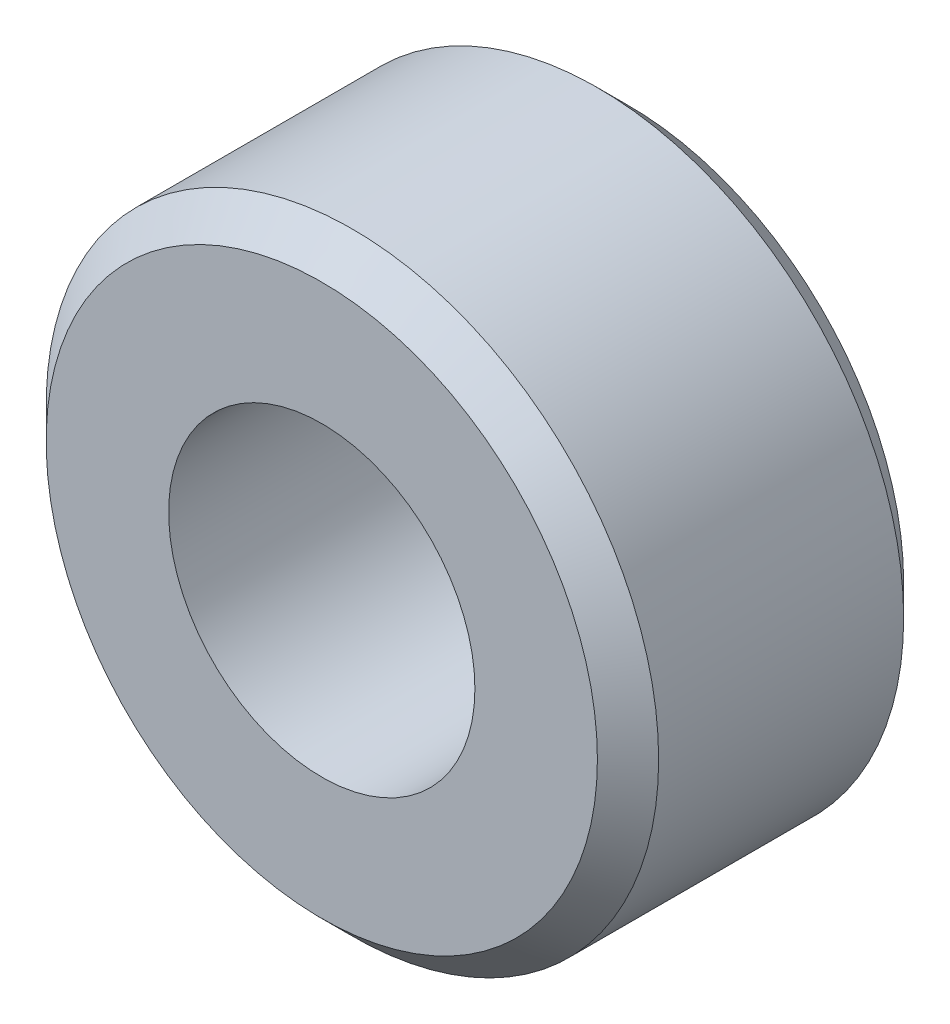
SolidWorks part; units mm, degrees
ref_plane "Płaszczyzna przednia" through (0, 0, 0) normal (0, 0, 1) x (1, 0, 0)
ref_plane "Płaszczyzna górna" through (0, 0, 0) normal (0, 1, 0) x (1, 0, 0)
ref_plane "Płaszczyzna prawa" through (0, 0, 0) normal (1, 0, 0) x (0, 0, -1)
sketch "Sketch1" plane through (0, 0, 0) normal (0, 0, 1) x (1, 0, 0)
  circle A0 centre (0, 0) radius 10
  circle A1 centre (0, 0) radius 5
  dimension "D1" = 20
  dimension "D2" = 10
extrude "Boss-Extrude1" add sketch "Sketch1" along normal blind 10
chamfer "Chamfer1" distance 1 angle 45 2 edges at (10, 0, 0) (10, 0, 10)
